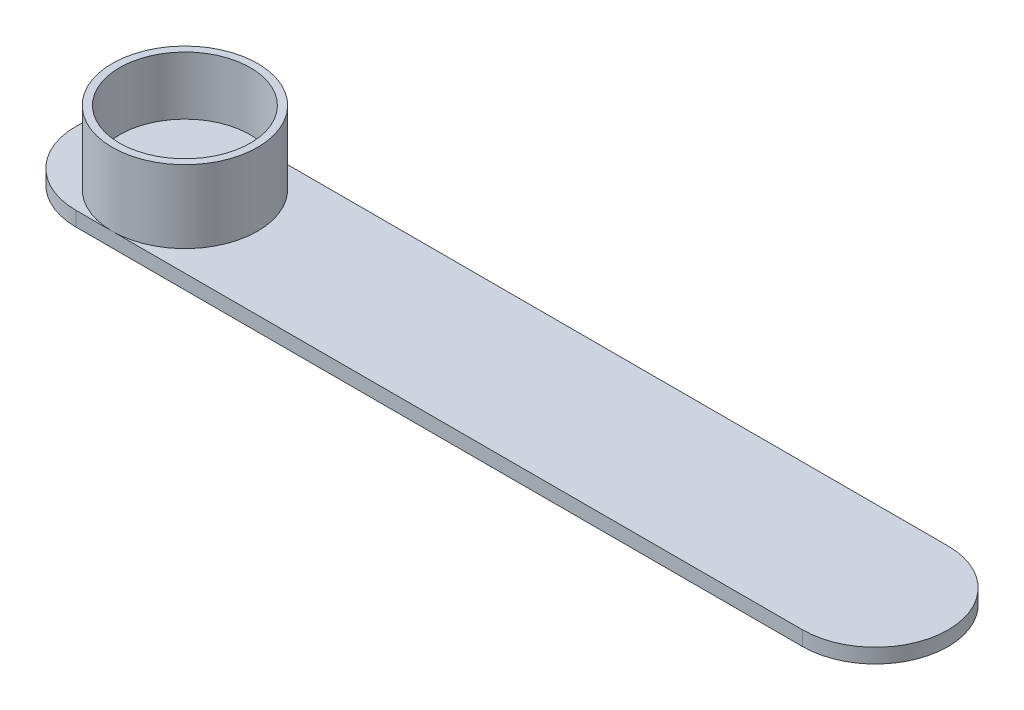
SolidWorks part; units mm, degrees
ref_plane "Front Plane" through (0, 0, 0) normal (0, 0, 1) x (1, 0, 0)
ref_plane "Top Plane" through (0, 0, 0) normal (0, 1, 0) x (1, 0, 0)
ref_plane "Right Plane" through (0, 0, 0) normal (1, 0, 0) x (0, 0, -1)
sketch "Sketch1" plane through (0, 0, 0) normal (0, 1, 0) x (1, 0, 0)
  line L1 (-30, -10) -> (70, -10)
  line L3 (-30, 10) -> (70, 10)
  arc A0 (-30, 10) -> (-30, -10) centre (-30, 0) ccw
  arc A1 (70, -10) -> (70, 10) centre (70, 0) ccw
  point P0 (0, 0)
  dimension "D3" = 20
  dimension "D5" = 20
  dimension "D1" = 100
extrude "Boss-Extrude1" add sketch "Sketch1" along normal blind 2
sketch "Sketch2" plane through (0, 2, 0) normal (0, 1, 0) x (1, 0, 0)
  circle A0 centre (-25, 0) radius 10
  arc A1 (-30, 10) -> (-30, -10) centre (-30, 0) ccw construction
  dimension "D1" = 20
  dimension "D2" = 5
extrude "Boss-Extrude2" add sketch "Sketch2" along normal blind 10
sketch "Sketch3" plane through (0, 12, 0) normal (0, 1, 0) x (1, 0, 0)
  circle A0 centre (-25, 0) radius 9
  circle A1 centre (-25, 0) radius 10 construction
  dimension "D1" = 0
  dimension "D2" = 18
extrude "Cut-Extrude1" cut sketch "Sketch3" against normal blind 8
